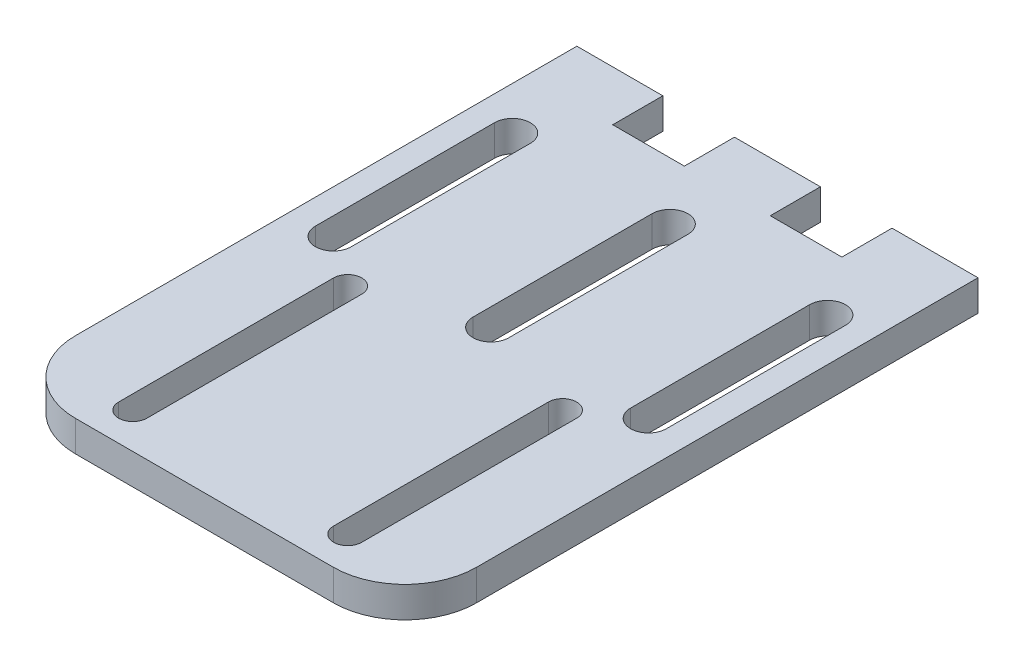
SolidWorks part; units mm, degrees
ref_plane "Front Plane" through (0, 0, 0) normal (0, 0, 1) x (1, 0, 0)
ref_plane "Top Plane" through (0, 0, 0) normal (0, 1, 0) x (1, 0, 0)
ref_plane "Right Plane" through (0, 0, 0) normal (1, 0, 0) x (0, 0, -1)
sketch "Sketch1" plane through (0, 0, 0) normal (0, 1, 0) x (1, 0, 0)
  line L0 (0, 0) -> (0, 80)
  line L1 (0, 80) -> (12, 80)
  line L2 (12, 80) -> (12, 73)
  line L3 (12, 73) -> (22, 73)
  line L4 (22, 73) -> (22, 80)
  line L5 (22, 80) -> (34, 80)
  line L6 (34, 80) -> (34, 73)
  line L7 (34, 73) -> (44, 73)
  line L8 (44, 73) -> (44, 80)
  line L9 (44, 80) -> (56, 80)
  line L10 (56, 80) -> (56, 0)
  line L11 (56, 0) -> (0, 0)
  line L12 (13, 35) -> (13, 5) construction
  line L13 (14.967, 35) -> (14.967, 5)
  line L14 (11.033, 35) -> (11.033, 5)
  line L15 (6, 65) -> (6, 40) construction
  line L16 (8.5, 65) -> (8.5, 40)
  line L17 (3.5, 65) -> (3.5, 40)
  line L18 (28, 80) -> (28, 0) construction
  line L19 (43, 35) -> (43, 5) construction
  line L20 (41.033, 35) -> (41.033, 5)
  line L21 (44.967, 35) -> (44.967, 5)
  line L22 (25.5, 65) -> (25.5, 40)
  line L23 (30.5, 65) -> (30.5, 40)
  line L24 (28, 65) -> (28, 40) construction
  line L25 (47.5, 65) -> (47.5, 40)
  line L26 (52.5, 65) -> (52.5, 40)
  line L27 (50, 65) -> (50, 40) construction
  arc A0 (14.967, 35) -> (11.033, 35) centre (13, 35) ccw
  arc A1 (11.033, 5) -> (14.967, 5) centre (13, 5) ccw
  arc A2 (8.5, 65) -> (3.5, 65) centre (6, 65) ccw
  arc A3 (3.5, 40) -> (8.5, 40) centre (6, 40) ccw
  arc A4 (41.033, 35) -> (44.967, 35) centre (43, 35) cw
  arc A5 (44.967, 5) -> (41.033, 5) centre (43, 5) cw
  arc A6 (30.5, 65) -> (25.5, 65) centre (28, 65) ccw
  arc A7 (25.5, 40) -> (30.5, 40) centre (28, 40) ccw
  arc A8 (52.5, 65) -> (47.5, 65) centre (50, 65) ccw
  arc A9 (47.5, 40) -> (52.5, 40) centre (50, 40) ccw
  point P15 (13, 20)
  point P20 (6, 52.5)
  point P31 (43, 20)
  point P36 (28, 52.5)
  point P44 (50, 52.5)
  point P51 (6, 80)
  dimension "D1" = 3.9339
  dimension "D2" = 30
  dimension "D3" = 5
  dimension "D4" = 25
  dimension "D5" = 80
  dimension "D6" = 7
  dimension "D7" = 12
  dimension "D8" = 10
  dimension "D9" = 30
  dimension "D10" = 5
  dimension "D12" = 15
  dimension "D13" = 3
extrude "Boss-Extrude1" add sketch "Sketch1" along normal blind 4.3
fillet "Fillet1" radius 10 2 edges at (56, 2.15, 0) (0, 2.15, 0)
equation "\"3ز2\"=2.86102"
